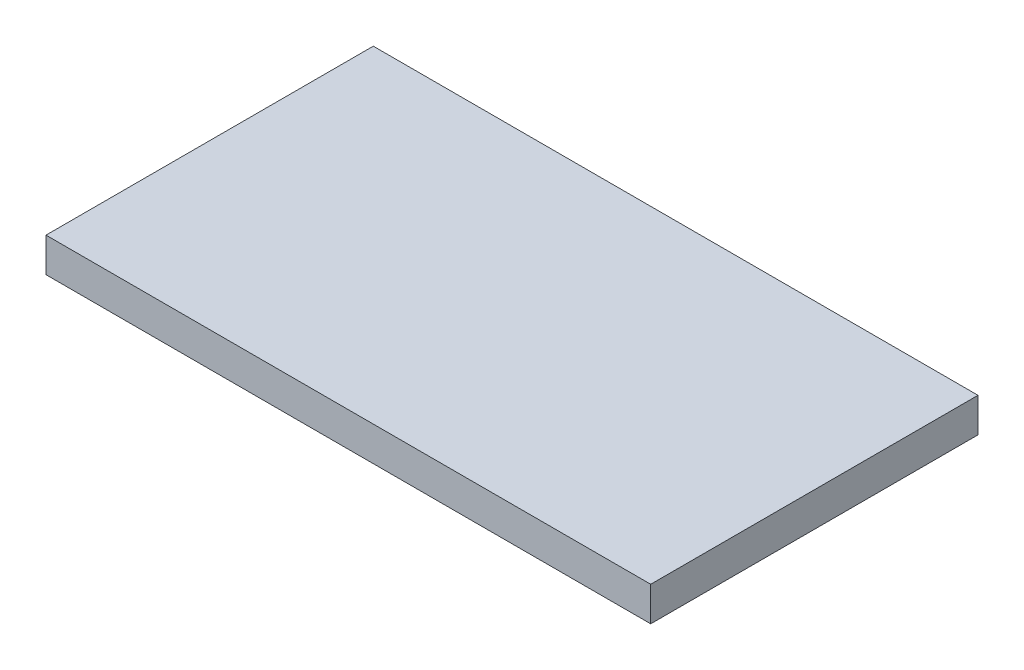
SolidWorks part; units mm, degrees
ref_plane "Front Plane" through (0, 0, 0) normal (0, 0, 1) x (1, 0, 0)
ref_plane "Top Plane" through (0, 0, 0) normal (0, 1, 0) x (1, 0, 0)
ref_plane "Right Plane" through (0, 0, 0) normal (1, 0, 0) x (0, 0, -1)
sketch "Sketch1" plane through (0, 0, 0) normal (0, 1, 0) x (1, 0, 0)
  line L1 (-123.19, -66.675) -> (123.19, -66.675)
  line L2 (-123.19, -66.675) -> (-123.19, 66.675)
  line L3 (-123.19, 66.675) -> (123.19, 66.675)
  line L4 (123.19, -66.675) -> (123.19, 66.675)
  line L5 (-123.19, -66.675) -> (123.19, 66.675) construction
  line L6 (-123.19, 66.675) -> (123.19, -66.675) construction
  point P0 (0, 0)
  dimension "D1" = 246.38
  dimension "D2" = 133.35
extrude "Boss-Extrude1" add sketch "Sketch1" along normal blind 13.97
